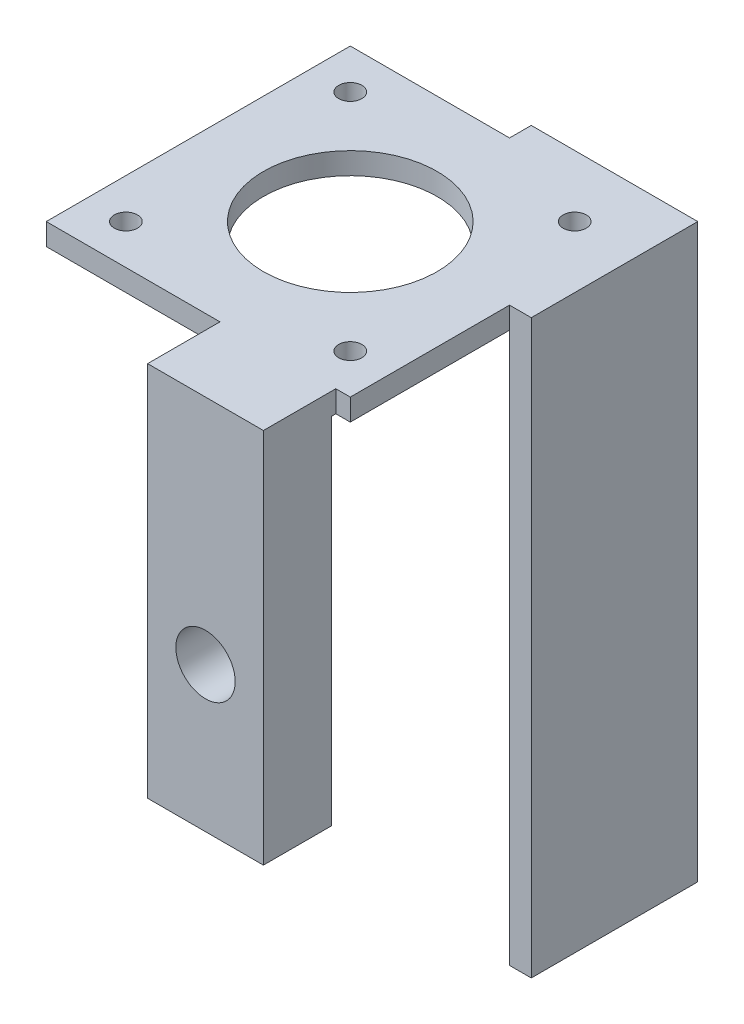
SolidWorks part; units mm, degrees
ref_plane "前视基准面" through (0, 0, 0) normal (0, 0, 1) x (1, 0, 0)
ref_plane "上视基准面" through (0, 0, 0) normal (0, 1, 0) x (1, 0, 0)
ref_plane "右视基准面" through (0, 0, 0) normal (1, 0, 0) x (0, 0, -1)
other "Configuration Table"
sketch "草图1" plane through (0, 0, 0) normal (0, 1, 0) x (1, 0, 0)
  line L1 (-21, -21) -> (21, -21)
  line L2 (-21, -21) -> (-21, 21)
  line L3 (-21, 21) -> (21, 21)
  line L4 (21, -21) -> (21, 21)
  line L5 (0, 21) -> (0, -21) construction
  line L6 (-21, 0) -> (21, 0) construction
  line L7 (-15.5, -15.5) -> (15.5, -15.5) construction
  line L8 (-15.5, -15.5) -> (-15.5, 15.5) construction
  line L9 (-15.5, 15.5) -> (15.5, 15.5) construction
  line L10 (15.5, -15.5) -> (15.5, 15.5) construction
  line L11 (0, 15.5) -> (0, -15.5) construction
  line L12 (-15.5, 0) -> (15.5, 0) construction
  circle A0 centre (15.5, 15.5) radius 1.6
  circle A1 centre (15.5, -15.5) radius 1.6
  circle A2 centre (-15.5, -15.5) radius 1.6
  circle A3 centre (-15.5, 15.5) radius 1.6
  circle A4 centre (0, 0) radius 12
  point P0 (0, 0)
  point P4 (0, 0)
  point P24 (0, 0)
  dimension "D3" = 31
  dimension "D5" = 3.2
  dimension "D7" = 24
  dimension "D1" = 42
  dimension "D2" = 42
  dimension "D4" = 31
  dimension "D6" = 4
extrude "凸台-拉伸1" add sketch "草图1" along normal blind 3
sketch "草图2" plane through (0, 0, 21) normal (0, 0, 1) x (1, 0, 0)
  line L0 (-21, 3) -> (21, 3) construction
  line L1 (19, 3) -> (3, 3)
  line L2 (19, 3) -> (19, -49)
  line L3 (19, -49) -> (3, -49)
  line L4 (3, 3) -> (3, -49)
  line L5 (21, 3) -> (21, 0) construction
  point P10 (11, 3)
  dimension "D3" = 10
  dimension "D1" = 52
  dimension "D2" = 16
extrude "凸台-拉伸2" add sketch "草图2" along normal blind 10
sketch "草图3" plane through (0, 0, 31) normal (0, 0, 1) x (1, 0, 0)
  line L0 (3, -49) -> (19, -49) construction
  line L1 (19, 3) -> (3, 3) construction
  circle A0 centre (11, -29) radius 4.1
  point P7 (11, -49)
  dimension "D1" = 8.2
  dimension "D2" = 32
extrude "切除-拉伸1" cut sketch "草图3" against normal blind 6
sketch "草图4" plane through (0, 3, 0) normal (0, 1, 0) x (1, 0, 0)
  line L1 (21, 21) -> (-21, 21) construction
  line L16 (21, -21) -> (21, 21) construction
  line L17 (1, 21) -> (21, 21)
  line L18 (1, 21) -> (1, 24)
  line L19 (1, 24) -> (24, 24)
  line L22 (24, 24) -> (24, 1)
  line L23 (24, 1) -> (21, 1)
  line L24 (21, 21) -> (21, 1)
  dimension "D1" = 3
  dimension "D2" = 3
  dimension "D3" = 23
  dimension "D4" = 23
  dimension "D5" = 0
extrude "凸台-拉伸3" add sketch "草图4" against normal blind 79
sketch "草图7" plane through (0, -49, 0) normal (0, -1, 0) x (1, 0, 0)
  line L4 (19, 31) -> (19, 21) construction
  line L5 (3, 21) -> (19, 21)
  line L6 (3, 21) -> (3, 21.6)
  line L7 (3, 21.6) -> (19, 21.6)
  line L8 (19, 21) -> (19, 21.6)
  dimension "D1" = 0.6
extrude "切除-拉伸4" cut sketch "草图7" against normal up to surface (49 mm away) up to face at (-15.5, 0, 17.1)
sketch "草图9" plane through (0, 0, 0) normal (0, -1, 0) x (1, 0, 0)
  line L0 (8.33, -15.1) -> (13.6672, -15.1)
  line L2 (13.6672, -15.1) -> (16.3, -17.7328)
  line L3 (16.3, -17.7328) -> (16.3, -19.3)
  line L4 (16.3, -19.3) -> (13.9, -19.3)
  line L5 (13.9, -19.3) -> (13.9, -21)
  line L6 (1, -21) -> (21, -21) construction
  line L7 (13.9, -21) -> (8.1, -21)
  line L8 (8.1, -21) -> (8.1, -19.3)
  line L9 (8.1, -19.3) -> (5.7, -19.3)
  line L10 (5.7, -19.3) -> (5.7, -17.73)
  line L11 (5.7, -17.73) -> (8.33, -15.1)
  line L12 (13.75, -14.9) -> (8.25, -14.9) construction
  line L14 (5.5, -17.65) -> (5.5, -19.5) construction
  line L15 (14.1, -19.5) -> (16.5, -19.5) construction
  line L16 (16.5, -17.65) -> (13.75, -14.9) construction
  line L18 (14.1, -20.5) -> (14.1, -19.5) construction
  line L19 (7.9, -19.5) -> (7.9, -20.5) construction
  line L20 (16.5, -19.5) -> (16.5, -17.65) construction
  line L21 (5.5, -19.5) -> (7.9, -19.5) construction
  line L24 (8.25, -14.9) -> (5.5, -17.65) construction
  point P22 (13.9, -20.15)
  dimension "D1" = 0.2
  dimension "D2" = 0.2
  dimension "D3" = 0.2
  dimension "D4" = 0.2
  dimension "D5" = 0.2
  dimension "D6" = 0.2
  dimension "D7" = 0.2
  dimension "D8" = 0.2
  dimension "D9" = 1.57
  dimension "D10" = 0
extrude "凸台-拉伸4" add sketch "草图9" along normal up to surface (26.6 mm away) from offset 49.4 up to face at (15.3333, -76, -15.3333)
ref_plane "基准面1" through (0, 0, 0) normal (-0.7071, 0, -0.7071) x (-0.7071, 0, 0.7071)
mirror "镜向1" about plane through (0, 0, 0) normal (-0.7071, 0, -0.7071) of "凸台-拉伸4"
sketch "草图10" plane through (0, -76, 0) normal (0, -1, 0) x (1, 0, 0)
  line L0 (8.1, -19.3) -> (8.1, -21) construction
  line L1 (21, -1) -> (21.1, -1)
  line L2 (21, -1) -> (21, -8.1)
  line L3 (21, -8.1) -> (21.1, -8.1)
  line L4 (21.1, -1) -> (21.1, -8.1)
  line L5 (21, -13.9) -> (21.1, -13.9)
  line L6 (21, -13.9) -> (21, -21.1)
  line L7 (21, -21.1) -> (21.1, -21.1)
  line L8 (21.1, -13.9) -> (21.1, -21.1)
  line L9 (13.9, -21) -> (21.1, -21)
  line L10 (13.9, -21) -> (13.9, -21.1)
  line L11 (13.9, -21.1) -> (21.1, -21.1)
  line L12 (21.1, -21) -> (21.1, -21.1)
  line L13 (1, -21) -> (8.1, -21)
  line L14 (1, -21) -> (1, -21.1)
  line L15 (1, -21.1) -> (8.1, -21.1)
  line L16 (8.1, -21) -> (8.1, -21.1)
  line M5 (21, -13.9) -> (21, -21)
  line M6 (21, -21) -> (13.9, -21)
  line M16 (8.1, -21) -> (1, -21)
  line M17 (1, -21) -> (1, -24)
  dimension "D1" = 0.1
  dimension "D2" = 0.1
  dimension "D3" = 0.1
  dimension "D4" = 0.1
extrude "切除-拉伸5" cut sketch "草图10" against normal up to surface (76 mm away) contours L16 L15 M16 M17 | L10 L11 L6 M6 | L9 L6 L7 L8 | L9 L8 L5 M5 up to face at (-15.5, 0, 17.1)
